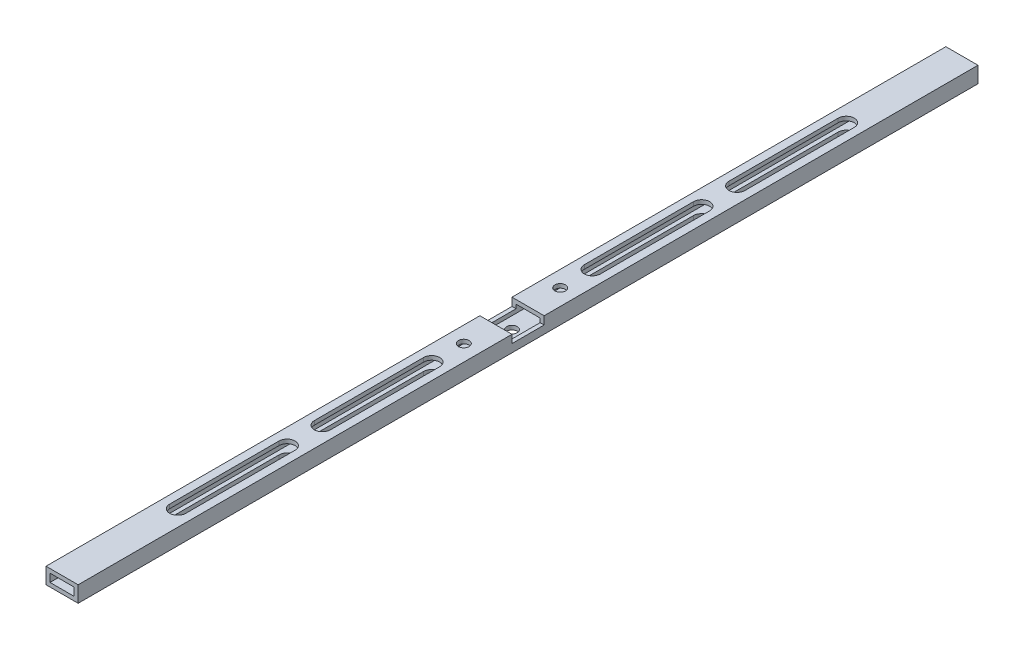
SolidWorks part; units mm, degrees
material "6061-T6 (SS)"
ref_plane "Front Plane" through (0, 0, 0) normal (0, 0, 1) x (1, 0, 0)
ref_plane "Top Plane" through (0, 0, 0) normal (0, 1, 0) x (1, 0, 0)
ref_plane "Right Plane" through (0, 0, 0) normal (1, 0, 0) x (0, 0, -1)
sketch "Sketch1" plane through (0, 0, 0) normal (0, 0, 1) x (1, 0, 0)
  line L1 (-6.35, -3.175) -> (6.35, -3.175)
  line L2 (-6.35, -3.175) -> (-6.35, 3.175)
  line L3 (-6.35, 3.175) -> (6.35, 3.175)
  line L4 (6.35, -3.175) -> (6.35, 3.175)
  line L5 (-6.35, -3.175) -> (6.35, 3.175) construction
  line L6 (-6.35, 3.175) -> (6.35, -3.175) construction
  line L7 (-4.7625, -1.5875) -> (4.7625, -1.5875)
  line L8 (-4.7625, -1.5875) -> (-4.7625, 1.5875)
  line L9 (-4.7625, 1.5875) -> (4.7625, 1.5875)
  line L10 (4.7625, -1.5875) -> (4.7625, 1.5875)
  line L11 (-4.7625, -1.5875) -> (4.7625, 1.5875) construction
  line L12 (-4.7625, 1.5875) -> (4.7625, -1.5875) construction
  point P0 (0, 0)
  point P6 (0, 0)
  dimension "D1" = 12.7
  dimension "D2" = 6.35
  dimension "D3" = 1.5875
  dimension "D4" = 1.5875
extrude "Boss-Extrude1" add sketch "Sketch1" along normal blind 355.6
sketch "Sketch2" plane through (0, 3.175, 0) normal (0, 1, 0) x (1, 0, 0)
  line L0 (-28.6201, -177.8) -> (50.4055, -177.8) construction
  line L1 (0, 14.638) -> (0, -377.4503) construction
  line L2 (-3.175, -209.55) -> (-3.175, -252.73)
  line L3 (-18.6635, -231.14) -> (41.2284, -231.14) construction
  line L4 (3.175, -209.55) -> (3.175, -252.73)
  arc A0 (3.175, -209.55) -> (-3.175, -209.55) centre (0, -209.55) ccw
  arc A1 (3.175, -252.73) -> (-3.175, -252.73) centre (0, -252.73) cw
  point P5 (0, -209.55)
  point P14 (3.175, -231.14)
  point P16 (-3.175, -231.14)
  dimension "D3" = 3.175
  dimension "D1" = 31.75
  dimension "D2" = 177.8
  dimension "D4" = 21.59
extrude "Cut-Extrude1" cut sketch "Sketch2" against normal blind 25.4
pattern_linear "LPattern1" count 2 spacing 57.15 along (0, 0, 1) of "Cut-Extrude1"
ref_plane "Plane1" through (0, 0, 177.8) normal (0, 0, 1) x (1, 0, 0)
mirror "Mirror1" about plane through (0, 0, 177.8) normal (0, 0, 1) of "LPattern1", "Cut-Extrude1"
sketch "Sketch3" plane through (6.35, 0, 0) normal (1, 0, 0) x (0, 0, -1)
  line L0 (-177.8, 47.6969) -> (-177.8, -57.2693) construction
  line L1 (-355.6, -3.175) -> (-355.6, 3.175) construction
  line L2 (-171.45, 3.175) -> (-184.15, 3.175)
  line L3 (-355.6, 3.175) -> (0, 3.175) construction
  line L4 (-184.15, 3.175) -> (-184.15, 0)
  line L5 (-184.15, 0) -> (-171.45, 0)
  line L6 (-171.45, 3.175) -> (-171.45, 0)
  point P12 (-177.8, 0)
  point P13 (-177.8, 3.175)
  dimension "D1" = 177.8
  dimension "D2" = 6.35
  dimension "D3" = 3.175
extrude "Cut-Extrude2" cut sketch "Sketch3" against normal blind 25.4
sketch "Sketch4" plane through (0, -3.175, 0) normal (0, -1, 0) x (-1, 0, 0)
  line L0 (-49.5512, -177.8) -> (67.9193, -177.8) construction
  line L1 (6.35, -355.6) -> (-6.35, -355.6) construction
  line L2 (0, 0) -> (0, -425.7626) construction
  circle A0 centre (0, -177.8) radius 2.0955
  circle A1 centre (0, -196.85) radius 2.0955
  circle A2 centre (0, -158.75) radius 2.0955
  dimension "D2" = 4.191
  dimension "D3" = 4.191
  dimension "D4" = 19.05
  dimension "D1" = 177.8
extrude "Cut-Extrude3" cut sketch "Sketch4" against normal blind 25.4
